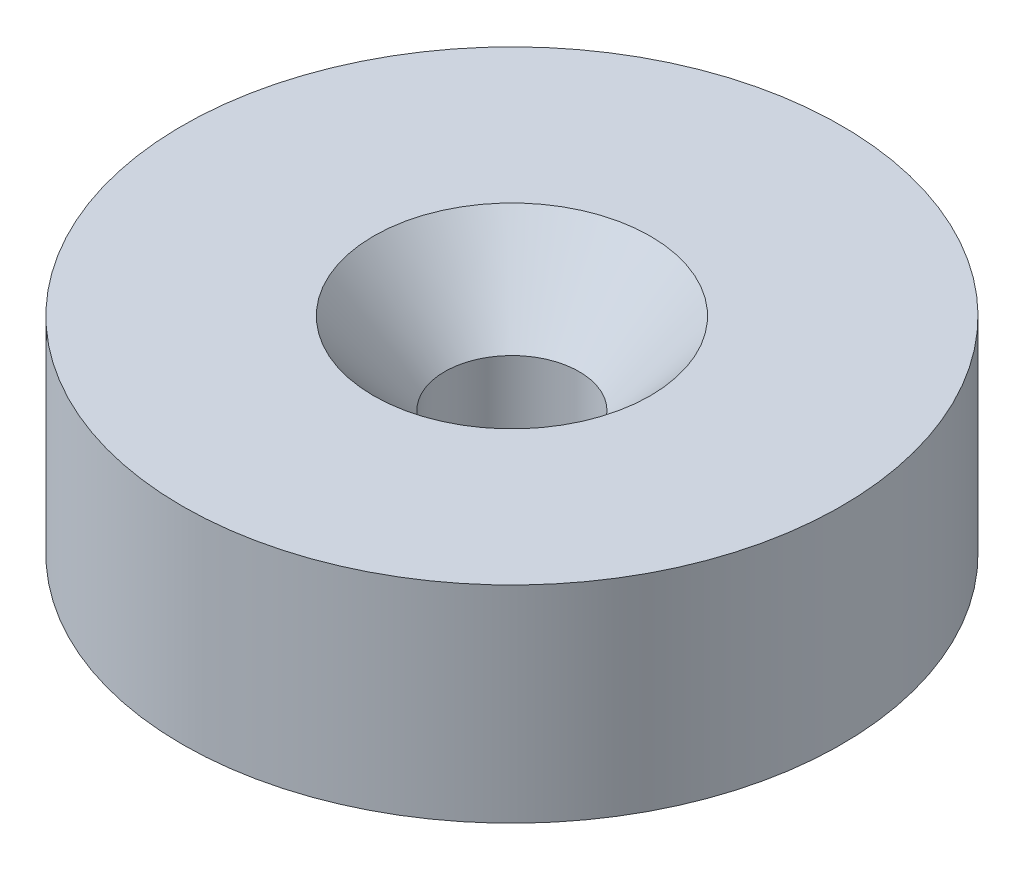
SolidWorks part; units mm, degrees
material "Nylon 6/10"
ref_plane "front" through (0, 0, 0) normal (0, 0, 1) x (1, 0, 0)
ref_plane "top" through (0, 0, 0) normal (0, 1, 0) x (1, 0, 0)
ref_plane "right" through (0, 0, 0) normal (1, 0, 0) x (0, 0, -1)
sketch "Sketch1" plane through (0, 0, 0) normal (0, 1, 0) x (1, 0, 0)
  circle A0 centre (0, 0) radius 12.7
  dimension "D1" = 25.4
extrude "Extrude1" add sketch "Sketch1" along normal blind 7.9502
hole_wizard "CSK for #10 Flat Head Machine Screw (100)1" positions "Sketch3" profile "Sketch2" countersink size "#10" standard "Ansi Inch" end condition through all
sketch "Sketch3" plane through (0, 7.9502, 0) normal (0, 1, 0) x (-1, 0, 0)
  point P0 (0, 0)
sketch "Sketch2" plane through (0, 7.9502, 0) normal (1, 0, 0) x (0, 0, 1)
  line L0 (0, 0) -> (0, 7.9502)
  line L1 (0, 7.9502) -> (2.5908, 7.9502)
  line L2 (2.5908, 7.9502) -> (2.5908, 3.1523)
  line L3 (2.5908, 3.1523) -> (5.3311, 0)
  line L5 (5.3311, 0) -> (0, 0)
  line L6 (-2.5908, 3.1523) -> (-5.3311, 0) construction
  line L11 (0, -6.35) -> (0, 107.95) construction
  dimension "Thru Hole Dia." = 5.1816
  dimension "Thru Hole Depth" = 7.9502
  dimension "Near C'Sink Dia." = 10.6622
  dimension "Near C'Sink Angle" = 82
